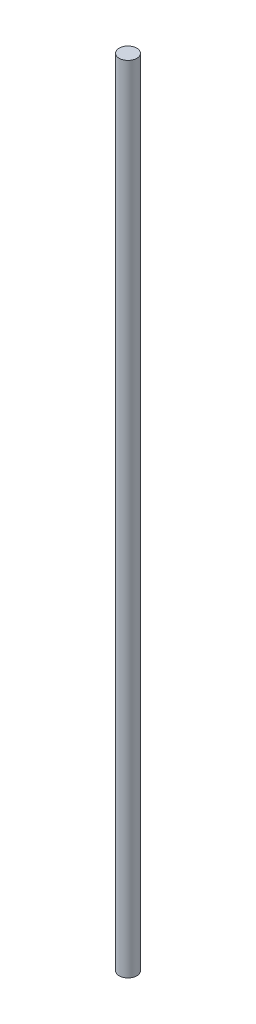
SolidWorks part; units mm, degrees
ref_plane "前基準面" through (0, 0, 0) normal (0, 0, 1) x (1, 0, 0)
ref_plane "上基準面" through (0, 0, 0) normal (0, 1, 0) x (1, 0, 0)
ref_plane "右基準面" through (0, 0, 0) normal (1, 0, 0) x (0, 0, -1)
sketch "草圖1" plane through (0, 0, 0) normal (0, 1, 0) x (1, 0, 0)
  circle A0 centre (0, 0) radius 5
  dimension "D1" = 10
extrude "填料-伸長1" add sketch "草圖1" along normal blind 450
